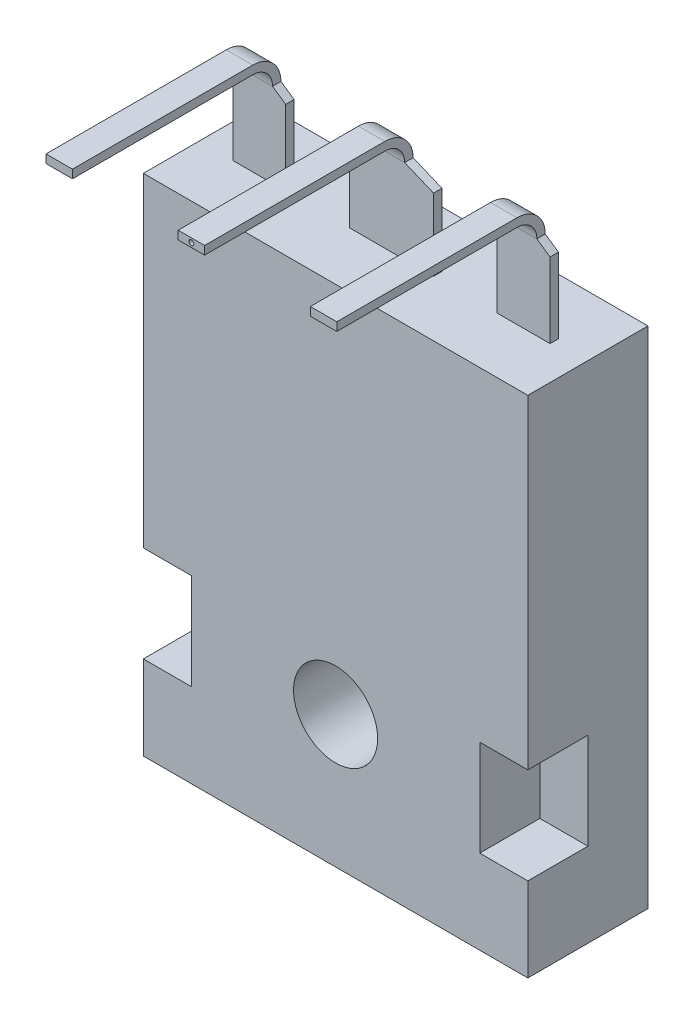
SolidWorks part; units mm, degrees
ref_plane "Спереди" through (0, 0, 0) normal (0, 0, 1) x (1, 0, 0)
ref_plane "Сверху" through (0, 0, 0) normal (0, 1, 0) x (1, 0, 0)
ref_plane "Справа" through (0, 0, 0) normal (1, 0, 0) x (0, 0, -1)
sketch "Эскиз1" plane through (0, 0, 0) normal (0, 0, 1) x (1, 0, 0)
  line L0 (0, -19.3209) -> (0, 33.6087) construction
  line L1 (-32.3098, 0) -> (29.0626, 0) construction
  line L3 (-8, -5.5) -> (8, -5.5)
  line L4 (-8, -5.5) -> (-8, 15.5)
  line L5 (-8, 15.5) -> (8, 15.5)
  line L6 (8, -5.5) -> (8, 15.5)
  circle A0 centre (0, 0) radius 1.75
  dimension "D4" = 3.5
  dimension "D1" = 16
  dimension "D2" = 21
  dimension "D3" = 11
extrude "Вытянуть1" add sketch "Эскиз1" along normal blind 5
sketch "Эскиз2" plane through (-8, 0, 0) normal (-1, 0, 0) x (0, 0, 1)
  line L0 (2.5, 7.3644) -> (2.5, 25.6142) construction
  line L1 (0, 15.5) -> (0, -5.5) construction
  line L2 (5, 15.5) -> (5, -5.5) construction
  line L3 (2.5, 15.5) -> (2.5, 19)
  line L4 (5, 15.5) -> (0, 15.5) construction
  line L6 (3.5, 20) -> (11, 20)
  arc A1 (2.5, 19) -> (3.5, 20) centre (3.5, 19) cw
  point P14 (2.5, 20)
  dimension "D2" = 11
  dimension "D1" = 1
  dimension "D3" = 20
extrude "Вытянуть-Тонкостенный1" add sketch "Эскиз2" against normal blind 16 thin thin type mid plane wall 0.35
sketch "Эскиз3" plane through (0, 0, 2.325) normal (0, 0, -1) x (-1, 0, 0)
  line L0 (0, 0) -> (0, 22.5231) construction
  line L1 (-1.75, 15.5) -> (-1.75, 18.5)
  line L2 (-8, 15.5) -> (8, 15.5) construction
  line L3 (-1.75, 18.5) -> (-0.55, 19)
  line L4 (-0.55, 19) -> (-0.55, 20.9379)
  line L5 (-8, 19) -> (8, 19) construction
  line L6 (0.55, 19) -> (0.55, 20.9379)
  line L7 (1.75, 18.5) -> (0.55, 19)
  line L8 (1.75, 15.5) -> (1.75, 18.5)
  line L9 (-5.5, 14.4406) -> (-5.5, 21.8466) construction
  line L10 (-4.95, 19) -> (-4.4, 18.6221)
  line L11 (-6.05, 19) -> (-6.05, 20.9379)
  line L12 (-6.05, 19) -> (-6.6, 18.6221)
  line L13 (-6.6, 18.6221) -> (-6.6, 15.5)
  line L14 (-4.95, 19) -> (-4.95, 20.9379)
  line L15 (-4.4, 18.6221) -> (-4.4, 15.5)
  line L16 (4.4, 18.6221) -> (4.4, 15.5)
  line L17 (4.95, 19) -> (4.4, 18.6221)
  line L18 (4.95, 19) -> (4.95, 20.9379)
  line L19 (6.05, 19) -> (6.05, 20.9379)
  line L20 (6.05, 19) -> (6.6, 18.6221)
  line L21 (6.6, 18.6221) -> (6.6, 15.5)
  line L22 (1.75, 15.5) -> (4.4, 15.5)
  line L23 (0.55, 20.9379) -> (4.95, 20.9379)
  line L24 (-0.55, 20.9379) -> (-4.95, 20.9379)
  line L25 (-6.6, 15.5) -> (-9.3209, 15.5)
  line L26 (-9.3209, 15.5) -> (-9.3209, 20.9379)
  line L27 (-9.3209, 20.9379) -> (-6.05, 20.9379)
  line L28 (6.05, 20.9379) -> (9.4998, 20.9379)
  line L29 (9.4998, 20.9379) -> (9.4998, 15.5)
  line L30 (9.4998, 15.5) -> (6.6, 15.5)
  line L31 (-4.4, 15.5) -> (-1.75, 15.5)
  dimension "D1" = 3
  dimension "D2" = 1.1
  dimension "D3" = 3.5
  dimension "D4" = 5.5
  dimension "D5" = 1.1
  dimension "D6" = 1.1
extrude "Вырез-Вытянуть1" cut sketch "Эскиз3" against normal blind 16
sketch "Эскиз4" plane through (0, 0, 5) normal (0, 0, -1) x (-1, 0, 0)
  line L0 (-11.0027, 0) -> (9.7903, 0) construction
  line L1 (0, 0) -> (0, 8.7015) construction
  line L2 (6, -2) -> (9.8191, -2)
  line L3 (6, -2) -> (6, 2)
  line L4 (6, 2) -> (9.8191, 2)
  line L5 (9.8191, -2) -> (9.8191, 2)
  line L6 (8, 15.5) -> (8, -5.5) construction
  line L7 (-9.8191, -2) -> (-9.8191, 2)
  line L8 (-6, 2) -> (-9.8191, 2)
  line L9 (-6, -2) -> (-6, 2)
  line L10 (-6, -2) -> (-9.8191, -2)
  dimension "D1" = 2
  dimension "D2" = 4
extrude "Вырез-Вытянуть2" cut sketch "Эскиз4" along normal blind 2.5
sketch "Эскиз5" plane through (0, 0, 11) normal (0, 0, 1) x (1, 0, 0)
  line L0 (0, 0) -> (0, 21.3988) construction
  line L1 (-0.9989, 20) -> (1.1243, 20) construction
  line L2 (0.55, 20.175) -> (-0.55, 20.175) construction
  line L3 (0.55, 19.825) -> (-0.55, 19.825) construction
  circle A0 centre (0, 20) radius 0.1
  dimension "D1" = 0.2
extrude "Вырез-Вытянуть3" cut sketch "Эскиз5" against normal blind 2
